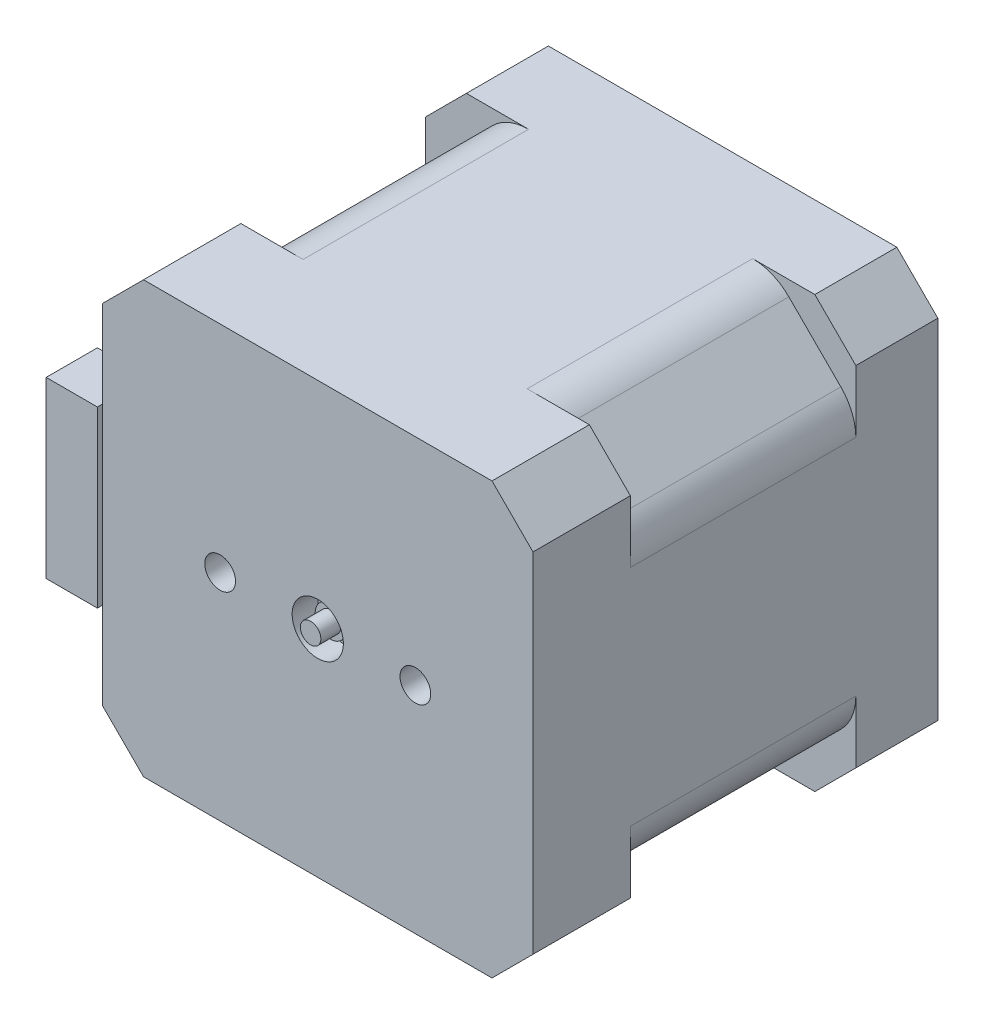
SolidWorks part; units mm, degrees
ref_plane "前视基准面" through (0, 0, 0) normal (0, 0, 1) x (1, 0, 0)
ref_plane "上视基准面" through (0, 0, 0) normal (0, 1, 0) x (1, 0, 0)
ref_plane "右视基准面" through (0, 0, 0) normal (1, 0, 0) x (0, 0, -1)
sketch "草图1" plane through (0, 0, 0) normal (0, 0, 1) x (1, 0, 0)
  line L0 (0, 38) -> (4, 42)
  line L1 (4, 0) -> (38, 0)
  line L2 (0, 4) -> (0, 38)
  line L3 (4, 42) -> (38, 42)
  line L4 (42, 4) -> (42, 38)
  line L5 (21, 42) -> (21, 0) construction
  line L6 (0, 21) -> (42, 21) construction
  line L7 (0, 4) -> (4, 0)
  line L8 (42, 38) -> (38, 42)
  line L9 (42, 4) -> (38, 0)
  dimension "D5" = 45
extrude "凸台-拉伸1" add sketch "草图1" against normal blind 8 contours L2 L0 L3 L8 L4 L9 L1 L7
sketch "草图2" plane through (0, 0, 0) normal (0, 0, 1) x (1, 0, 0)
  line L0 (0, 21) -> (42, 21) construction
  line L1 (0, 4) -> (0, 38) construction
  line L2 (42, 4) -> (42, 38) construction
  line L3 (21, 42) -> (21, 0) construction
  line L4 (4, 42) -> (38, 42) construction
  line L5 (4, 0) -> (38, 0) construction
  circle A0 centre (5.5, 36.5) radius 1.5
  circle A1 centre (5.5, 5.5) radius 1.5
  circle A2 centre (36.5, 36.5) radius 1.5
  circle A3 centre (36.5, 5.5) radius 1.5
  dimension "D3" = 3
  dimension "D1" = 31
  dimension "D2" = 31
extrude "切除-拉伸1" cut sketch "草图2" against normal up to next
sketch "草图5" plane through (0, 0, 0) normal (0, 0, 1) x (1, 0, 0)
  line L8 (0, 4) -> (4, 0)
  line L9 (4, 0) -> (38, 0)
  line L10 (38, 0) -> (42, 4)
  line L11 (42, 4) -> (42, 38)
  line L12 (42, 38) -> (38, 42)
  line L13 (38, 42) -> (4, 42)
  line L14 (4, 42) -> (0, 38)
  line L15 (0, 38) -> (0, 4)
  line L16 (0, 4) -> (4, 0)
  line L17 (4, 0) -> (38, 0)
  line L18 (38, 0) -> (42, 4)
  line L19 (42, 4) -> (42, 38)
  line L20 (42, 38) -> (38, 42)
  line L21 (38, 42) -> (4, 42)
  line L22 (4, 42) -> (0, 38)
  line L23 (0, 38) -> (0, 4)
  dimension "D1" = 0
extrude "凸台-拉伸2" add sketch "草图5" along normal blind 22
sketch "草图6" plane through (0, 0, 22) normal (0, 0, 1) x (1, 0, 0)
  line L0 (0, 34) -> (8, 42)
  line L1 (0, 38) -> (0, 4) construction
  line L2 (38, 42) -> (4, 42) construction
  line L3 (0, 21) -> (42, 21) construction
  line L4 (42, 4) -> (42, 38) construction
  line L5 (21, 21) -> (21, 42) construction
  line L6 (21, 21) -> (21, 0) construction
  line L7 (4, 0) -> (38, 0) construction
  line L8 (42, 34) -> (34, 42)
  line L9 (0, 8) -> (8, 0)
  line L10 (42, 8) -> (34, 0)
  line L20 (0, 38) -> (0, 4)
  line L21 (0, 4) -> (4, 0)
  line L22 (4, 0) -> (38, 0)
  line L23 (38, 0) -> (42, 4)
  line L24 (42, 4) -> (42, 38)
  line L25 (42, 38) -> (38, 42)
  line L26 (38, 42) -> (4, 42)
  line L27 (4, 42) -> (0, 38)
  line L28 (0, 38) -> (0, 4)
  line L29 (0, 4) -> (4, 0)
  line L30 (4, 0) -> (38, 0)
  line L31 (38, 0) -> (42, 4)
  line L32 (42, 4) -> (42, 38)
  line L33 (42, 38) -> (38, 42)
  line L34 (38, 42) -> (4, 42)
  line L35 (4, 42) -> (0, 38)
  line M17 (0, 38) -> (0, 4)
  line M18 (0, 4) -> (4, 0)
  line M19 (4, 0) -> (38, 0)
  line M20 (38, 0) -> (42, 4)
  line M21 (42, 4) -> (42, 38)
  line M22 (42, 38) -> (38, 42)
  line M23 (38, 42) -> (4, 42)
  line M24 (4, 42) -> (0, 38)
  dimension "D1" = 45
  dimension "D2" = 8
  dimension "D3" = 0
extrude "切除-拉伸2" cut sketch "草图6" against normal blind 22 contours L9 M17 M18 M19 | L10 M21 M19 M20 | L8 M21 M22 M23 | L0 M17 M23 M24
sketch "草图7" plane through (0, 0, 22) normal (0, 0, 1) x (1, 0, 0)
  line L0 (0, 38) -> (0, 4)
  line L1 (0, 4) -> (4, 0)
  line L2 (4, 0) -> (38, 0)
  line L3 (38, 0) -> (42, 4)
  line L4 (42, 4) -> (42, 38)
  line L5 (42, 38) -> (38, 42)
  line L6 (38, 42) -> (4, 42)
  line L7 (4, 42) -> (0, 38)
  line L8 (4, 42) -> (0, 38) construction
  line L9 (42, 38) -> (38, 42) construction
  line L10 (0, 4) -> (4, 0) construction
  line L11 (38, 0) -> (42, 4) construction
  line L14 (8, 0) -> (34, 0) construction
  line L15 (0, 34) -> (0, 8) construction
  line L16 (42, 8) -> (42, 34) construction
  line L17 (4, 42) -> (38, 42) construction
extrude "凸台-拉伸3" add sketch "草图7" along normal blind 9.5 contours L7 L0 L1 L2 L3 L4 L5 L6
sketch "草图8" plane through (0, 0, 31.5) normal (0, 0, 1) x (1, 0, 0)
  line L0 (0, 21) -> (42, 21) construction
  line L1 (0, 38) -> (0, 4) construction
  line L2 (42, 4) -> (42, 38) construction
  line L3 (21, 42) -> (21, 0) construction
  line L4 (38, 42) -> (4, 42) construction
  line L5 (4, 0) -> (38, 0) construction
  circle A0 centre (11.475, 21) radius 1.5
  circle A1 centre (30.525, 21) radius 1.5
  circle A2 centre (21, 21) radius 1
  circle A3 centre (21, 21) radius 2.5
  dimension "D1" = 3
  dimension "D3" = 2
  dimension "D4" = 5
  dimension "D2" = 19.05
extrude "切除-拉伸3" cut sketch "草图8" against normal blind 5 contours A0 | A1
sketch "草图10" plane through (0, 0, 31.5) normal (0, 0, 1) x (1, 0, 0)
  line L0 (0, 21) -> (42, 21) construction
  line L1 (0, 38) -> (0, 4) construction
  line L2 (42, 4) -> (42, 38) construction
  line L3 (21, 42) -> (21, 0) construction
  line L4 (38, 42) -> (4, 42) construction
  line L5 (4, 0) -> (38, 0) construction
  circle A0 centre (21, 21) radius 2.5
  circle A1 centre (21, 21) radius 1
  dimension "D1" = 5
  dimension "D2" = 2
extrude "切除-拉伸4" cut sketch "草图10" against normal blind 2.5 contours A0
sketch "草图11" plane through (0, 0, 29) normal (0, 0, 1) x (1, 0, 0)
  circle A0 centre (21, 21) radius 1.5
  point P0 (21, 21)
  dimension "D1" = 3
extrude "凸台-拉伸4" add sketch "草图11" along normal blind 1.25 contours A0
sketch "草图12" plane through (0, 0, 30.25) normal (0, 0, 1) x (1, 0, 0)
  circle A0 centre (21, 21) radius 1
  dimension "D1" = 2
extrude "凸台-拉伸5" add sketch "草图12" along normal blind 1.95
fillet "圆角3" radius 5 8 edges at (0, 34, 11) (8, 42, 11) (34, 42, 11) (42, 34, 11) (42, 8, 11) (34, 0, 11) (8, 0, 11) (0, 8, 11)
sketch "草图13" plane through (0, 0, -8) normal (0, 0, -1) x (-1, 0, 0)
  line L0 (-42, 21) -> (0, 21) construction
  line L1 (-42, 4) -> (-42, 38) construction
  line L2 (0, 4) -> (0, 38) construction
  circle A0 centre (-21, 21) radius 12.5
  dimension "D1" = 25
extrude "凸台-拉伸6" add sketch "草图13" along normal blind 2 contours A0
sketch "草图14" plane through (0, 0, -10) normal (0, 0, -1) x (-1, 0, 0)
  circle A0 centre (-21, 21) radius 2.5
  point P0 (-21, 21)
  dimension "D1" = 5
extrude "凸台-拉伸7" add sketch "草图14" along normal blind 11
sketch "草图16" plane through (0, 0, -21) normal (0, 0, -1) x (-1, 0, 0)
  line L0 (-23.5, 21) -> (-18.5, 21) construction
  line L1 (-22.5, 23) -> (-19.5, 23)
  circle A0 centre (-21, 21) radius 2.5 construction
  circle A1 centre (-21, 21) radius 2.5 construction
  dimension "D1" = 2
extrude "切除-拉伸5" cut sketch "草图16" against normal blind 9.8 and the other way through all
sketch "草图17" plane through (0, 0, 0) normal (-1, 0, 0) x (0, 0, 1)
  line L0 (31.5, 21) -> (-8, 21) construction
  line L1 (31.5, 38) -> (31.5, 4) construction
  line L2 (-8, 4) -> (-8, 38) construction
  line L4 (27.5, 13) -> (31.5, 13)
  line L5 (27.5, 29) -> (31.5, 29)
  line L6 (31.5, 13) -> (31.5, 29)
  line L7 (27.5, 13) -> (27.5, 15)
  line L8 (27.5, 29) -> (27.5, 27)
  point P11 (27.5, 21)
  dimension "D1" = 4
  dimension "D2" = 8
  dimension "D3" = 2
extrude "拉伸-薄壁6" add sketch "草图17" along normal blind 5 thin thin type mid plane wall 1
sketch "草图18" plane through (0, 15, 0) normal (0, 1, 0) x (1, 0, 0)
  line L0 (-5, -28) -> (0, -28) construction
  line L1 (0, -27) -> (-1, -27)
  line L2 (0, -27) -> (0, -28)
  line L3 (0, -28) -> (-1, -28)
  line L4 (-1, -27) -> (-1, -28)
  dimension "D1" = 1
extrude "凸台-拉伸8" add sketch "草图18" along normal up to next
